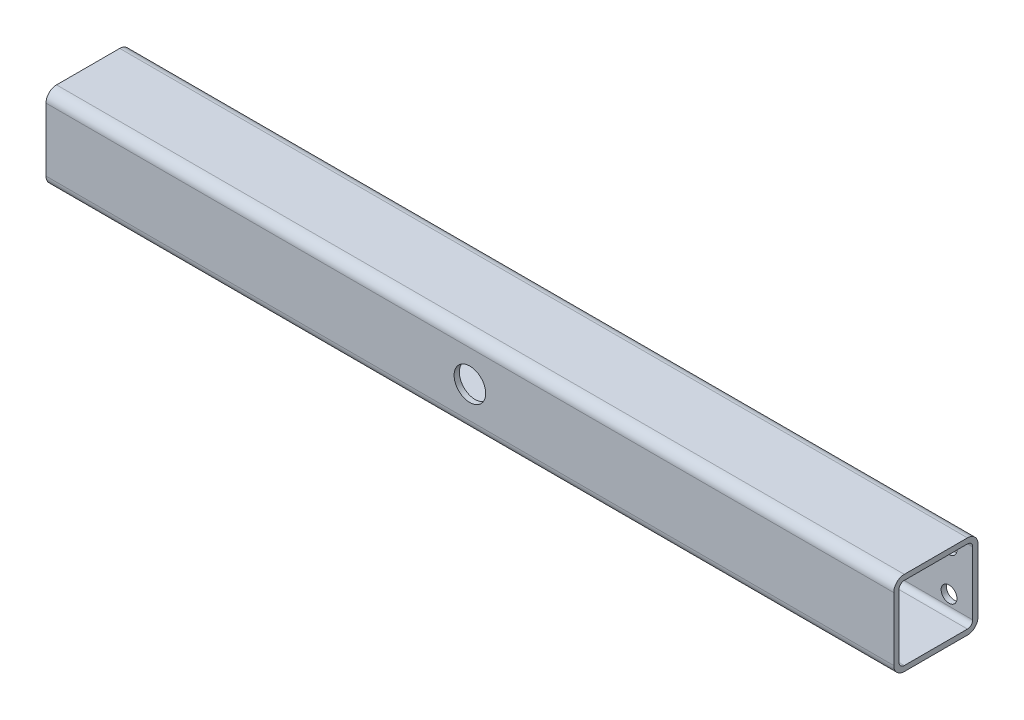
SolidWorks part; units mm, degrees
ref_plane "front" through (0, 0, 0) normal (0, 0, 1) x (1, 0, 0)
ref_plane "top" through (0, 0, 0) normal (0, 1, 0) x (1, 0, 0)
ref_plane "right" through (0, 0, 0) normal (1, 0, 0) x (0, 0, -1)
sketch "Sketch1" plane through (0, 0, 0) normal (1, 0, 0) x (0, 0, -1)
  line L0 (-127, 127) -> (-50.8, 50.8) construction
  line L1 (-127, 139.7) -> (-50.8, 139.7)
  line L2 (-139.7, 127) -> (-139.7, 50.8)
  line L3 (-127, 38.1) -> (-50.8, 38.1)
  line L4 (-38.1, 127) -> (-38.1, 50.8)
  line L5 (-127, 133.35) -> (-50.8, 133.35)
  line L6 (-44.45, 127) -> (-44.45, 50.8)
  line L7 (-127, 44.45) -> (-50.8, 44.45)
  line L8 (-133.35, 127) -> (-133.35, 50.8)
  arc A0 (-38.1, 50.8) -> (-50.8, 38.1) centre (-50.8, 50.8) cw
  arc A1 (-38.1, 127) -> (-50.8, 139.7) centre (-50.8, 127) ccw
  arc A2 (-139.7, 127) -> (-127, 139.7) centre (-127, 127) cw
  arc A3 (-127, 38.1) -> (-139.7, 50.8) centre (-127, 50.8) cw
  arc A4 (-133.35, 127) -> (-127, 133.35) centre (-127, 127) cw
  arc A5 (-44.45, 127) -> (-50.8, 133.35) centre (-50.8, 127) ccw
  arc A6 (-44.45, 50.8) -> (-50.8, 44.45) centre (-50.8, 50.8) cw
  arc A7 (-127, 44.45) -> (-133.35, 50.8) centre (-127, 50.8) cw
  point P12 (-88.9, 88.9)
  dimension "D3" = 12.7
  dimension "D1" = 101.6
  dimension "D2" = 101.6
  dimension "D4" = 88.9
  dimension "D5" = 88.9
  dimension "D6" = 6.35
extrude "Base-Extrude" add sketch "Sketch1" along normal mid plane 1022.35
sketch "mates" plane through (0, 139.7, 0) normal (0, 1, 0) x (-1, 0, 0)
  line L0 (-511.175, 88.9) -> (511.175, 88.9) construction
  line L1 (-511.175, 50.8) -> (-511.175, 127) construction
  line L2 (511.175, 50.8) -> (511.175, 127) construction
  point P6 (-349.25, 88.9)
  point P7 (349.25, 88.9)
  dimension "D1" = 349.25
  dimension "D2" = 349.25
sketch "Sketch2" plane through (0, 0, 38.1) normal (0, 0, -1) x (-1, 0, 0)
  line L0 (-511.175, 88.9) -> (511.175, 88.9) construction
  line L1 (511.175, 50.8) -> (511.175, 127) construction
  line L2 (-511.175, 50.8) -> (-511.175, 127) construction
  point P6 (0, 88.9)
  point P7 (482.6, 88.9)
  point P8 (-482.6, 88.9)
  dimension "D1" = 965.2
  dimension "D2" = 482.6
sketch "Sketch3" plane through (0, 0, 139.7) normal (0, 0, 1) x (1, 0, 0)
  line L0 (511.175, 38.1) -> (-511.175, 38.1) construction
  circle A0 centre (0, 88.9) radius 19.05
  dimension "D1" = 38.1
  dimension "D2" = 50.8
extrude "Cut-Extrude1" cut sketch "Sketch3" against normal blind 25.4
sketch "Sketch4" plane through (0, 0, 38.1) normal (0, 0, -1) x (-1, 0, 0)
  line L0 (-511.175, 50.8) -> (-511.175, 127) construction
  line L1 (-500.0498, 127) -> (-465.1375, 127) construction
  line L2 (-508, 119.0498) -> (-508, 58.7502) construction
  line L3 (-500.0498, 50.8) -> (-465.1375, 50.8) construction
  line L4 (-457.2, 119.0625) -> (-457.2, 58.7375) construction
  line L5 (-511.175, 127) -> (-511.175, 50.8) construction
  arc A0 (-457.2, 119.0625) -> (-465.1375, 127) centre (-465.1375, 119.0625) ccw construction
  arc A1 (-465.1375, 50.8) -> (-457.2, 58.7375) centre (-465.1375, 58.7375) ccw construction
  circle A2 centre (-482.6, 63.5) radius 9.525
  arc A3 (-508, 119.0498) -> (-500.0498, 127) centre (-500.0498, 119.0498) cw construction
  arc A4 (-500.0498, 50.8) -> (-508, 58.7502) centre (-500.0498, 58.7502) cw construction
  circle A5 centre (-482.6, 114.3) radius 9.525
  point P6 (-511.175, 88.9)
  point P18 (-508, 88.9)
  point P23 (-482.5936, 88.9)
  point P24 (-482.5936, 127)
  dimension "D3" = 7.9375
  dimension "D4" = 19.05
  dimension "D7" = 7.9502
  dimension "D1" = 50.8
  dimension "D2" = 76.2
  dimension "D5" = 482.6
  dimension "D6" = 63.5
  dimension "D8" = 3.175
  dimension "D9" = 50.8
extrude "Cut-Extrude2" cut sketch "Sketch4" against normal blind 25.4
sketch "Sketch5" plane through (0, 38.1, 0) normal (0, -1, 0) x (1, 0, 0)
  line L0 (511.175, 139.7) -> (-511.175, 139.7) construction
  circle A0 centre (482.6, 120.65) radius 3.9751
  dimension "D3" = 7.9502
  dimension "D1" = 482.6
  dimension "D2" = 19.05
extrude "Cut-Extrude3" cut sketch "Sketch5" against normal blind 25.4
mirror "Mirror1" about plane through (0, 0, 0) normal (1, 0, 0) of "Cut-Extrude3", "Cut-Extrude2"
sketch "Sketch6" plane through (0, 0, 38.1) normal (0, 0, -1) x (-1, 0, 0)
  circle A0 centre (482.6, 63.5) radius 9.525 construction
  point P0 (482.6, 63.5)
